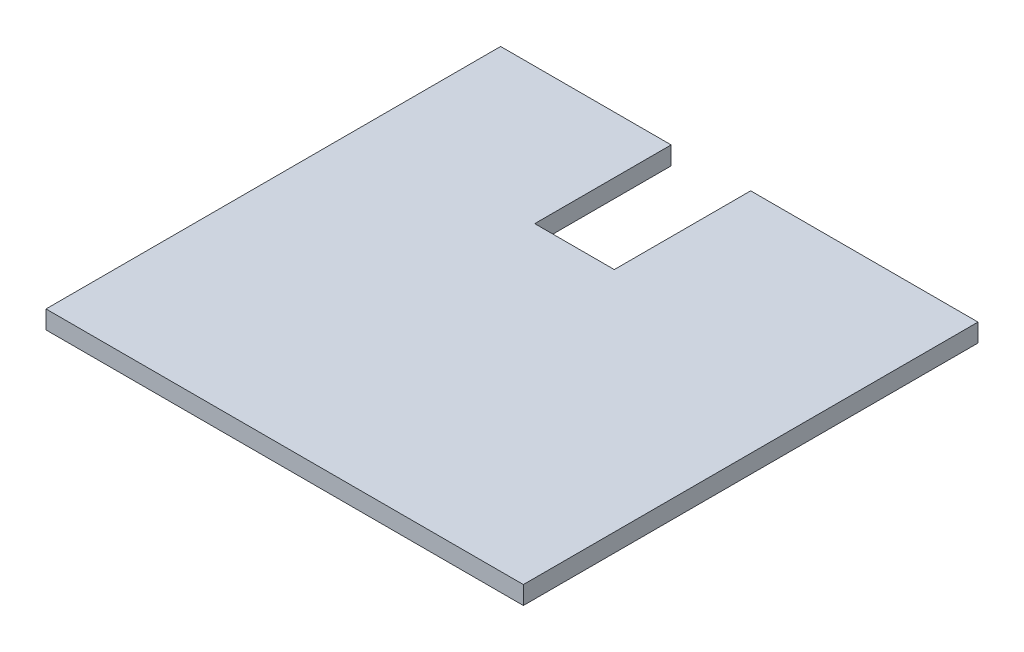
SolidWorks part; units mm, degrees
ref_plane "Front Plane" through (0, 0, 0) normal (0, 0, 1) x (1, 0, 0)
ref_plane "Top Plane" through (0, 0, 0) normal (0, 1, 0) x (1, 0, 0)
ref_plane "Right Plane" through (0, 0, 0) normal (1, 0, 0) x (0, 0, -1)
sketch "Sketch2" plane through (0, 0, 0) normal (0, 1, 0) x (1, 0, 0)
  line L0 (-9.1262, 8.301) -> (-1.6262, 8.301)
  line L1 (-1.6262, 8.301) -> (-1.6262, 2.301)
  line L2 (-1.6262, 2.301) -> (1.8738, 2.301)
  line L3 (1.8738, 2.301) -> (1.8738, 8.301)
  line L4 (1.8738, 8.301) -> (11.8738, 8.301)
  line L5 (11.8738, 8.301) -> (11.8738, -11.699)
  line L6 (11.8738, -11.699) -> (-9.1262, -11.699)
  line L7 (-9.1262, -11.699) -> (-9.1262, 8.301)
  dimension "D1" = 20
  dimension "D2" = 6
  dimension "D3" = 20
  dimension "D4" = 3.5
  dimension "D5" = 7.5
  dimension "D6" = 10
extrude "Boss-Extrude1" add sketch "Sketch2" along normal blind 0.8
